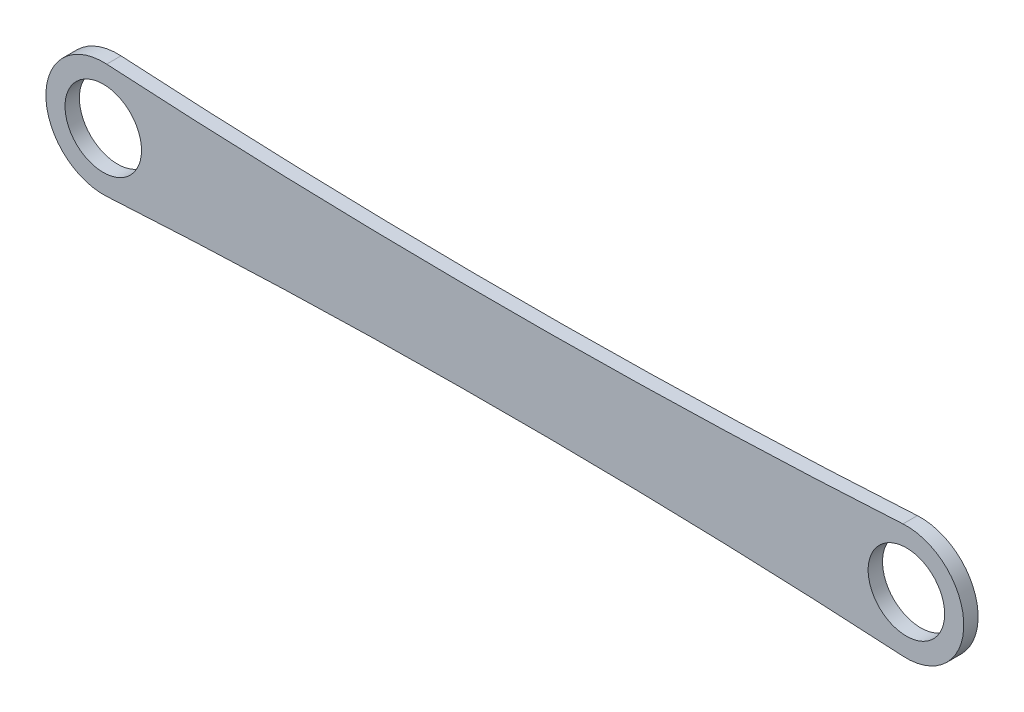
SolidWorks part; units mm, degrees
ref_plane "Front Plane" through (0, 0, 0) normal (0, 0, 1) x (1, 0, 0)
ref_plane "Top Plane" through (0, 0, 0) normal (0, 1, 0) x (1, 0, 0)
ref_plane "Right Plane" through (0, 0, 0) normal (1, 0, 0) x (0, 0, -1)
sketch "Sketch1" plane through (0, 0, 0) normal (0, 0, 1) x (1, 0, 0)
  line L0 (-80.9189, 0) -> (84, 0) construction
  circle A0 centre (0, 0) radius 4
  circle A1 centre (84, 0) radius 4
  arc A2 (0.3569, 5.9894) -> (0.3569, -5.9894) centre (0, 0) ccw
  arc A3 (83.6431, -5.9894) -> (83.6431, 5.9894) centre (84, 0) ccw
  arc A4 (0.3569, 5.9894) -> (83.6431, 5.9894) centre (42, 704.7496) ccw
  arc A5 (0.3569, -5.9894) -> (83.6431, -5.9894) centre (42, -704.7496) cw
  dimension "D2" = 8
  dimension "D3" = 8
  dimension "D4" = 12
  dimension "D5" = 12
  dimension "D6" = 700
  dimension "D7" = 700
  dimension "D1" = 84
extrude "Boss-Extrude1" add sketch "Sketch1" along normal blind 1.5
